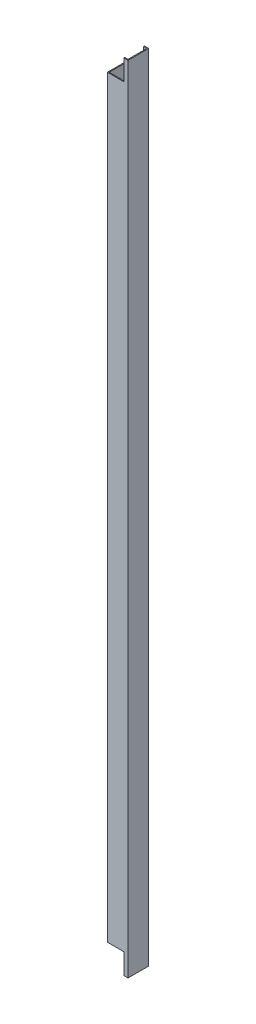
SolidWorks part; units mm, degrees
ref_plane "Front Plane" through (0, 0, 0) normal (0, 0, 1) x (1, 0, 0)
ref_plane "Top Plane" through (0, 0, 0) normal (0, 1, 0) x (1, 0, 0)
ref_plane "Right Plane" through (0, 0, 0) normal (1, 0, 0) x (0, 0, -1)
sketch "Sketch1" plane through (0, 0, 0) normal (0, 1, 0) x (1, 0, 0)
  line L0 (0, 0) -> (0, 50)
  line L1 (0, 50) -> (50, 50)
  line L2 (50, 50) -> (50, 0)
  line L3 (50, 0) -> (0, 0)
  line L4 (2.2, 47.8) -> (47.8, 47.8)
  line L5 (47.8, 47.8) -> (47.8, 2.2)
  line L6 (47.8, 2.2) -> (2.2, 2.2)
  line L7 (2.2, 2.2) -> (2.2, 47.8)
  dimension "D1" = 50
  dimension "D2" = 50
  dimension "D3" = 2.2
extrude "Boss-Extrude1" add sketch "Sketch1" along normal blind 1923
sketch "Sketch2" plane through (0, 0, 0) normal (0, 0, 1) x (1, 0, 0)
  line L0 (0, 0) -> (0, 50)
  line L1 (0, 1923) -> (0, 0) construction
  line L2 (0, 50) -> (40, 50)
  line L3 (40, 50) -> (40, 0)
  line L5 (40, 0) -> (0, 0)
  line L6 (0, 1923) -> (40, 1923)
  line L7 (0, 1923) -> (50, 1923) construction
  line L8 (40, 1923) -> (40, 1873)
  line L9 (40, 1873) -> (0, 1873)
  line L10 (0, 1873) -> (0, 1923)
  dimension "D1" = 50
  dimension "D2" = 40
  dimension "D3" = 50
  dimension "D4" = 40
extrude "Cut-Extrude2" cut sketch "Sketch2" against normal blind 50
equation "\"SquareTube_length\"=1923.0"
equation "\"D1@Boss-Extrude1\"=\"SquareTube_length\""
equation "\"SquareTube_inFront1_cutDepth50_R\"=0.5"
equation "\"D1@Sketch2\"= \"SquareTube_inFront11_cutDepth50_R\""
equation "\"SquareTube_inFront1_cutDepth50_L\"=0.5"
equation "\"D3@Sketch2\"= \"SquareTube_inFront11_cutDepth50_L\""
equation "\"CarBeamWidth\"=700.0"
equation "\"MetalSheet_3mm_length\"=5030.0"
equation "\"MetalSheet_3mm_width\"=1923.0"
equation "\"MetalSheet_3mm_FloorCut_L_length\"=1764.0"
equation "\"MetalSheet_3mm_FloorCut_L_disdance\"=1665.0"
equation "\"MetalSheet_3mm_FloorCut_R_length\"=1764.0"
equation "\"MetalSheet_3mm_FloorCut_R_disdance\"=1665.0"
equation "\"indoorHeight\"=1940.0"
equation "\"x\"=66.0"
equation "\"da\"=62.0"
equation "\"SquareTube_wheel_length\"= 750"
equation "\"channelSteel_length\"=5030.0"
equation "\"SquareTube_inFront2_cutDepth50_R\"=0.5"
equation "\"SquareTube_inFront2_cutDepth50_L\"=0.5"
equation "\"SquareTube_inFront3_cutDepth50_R\"=0.5"
equation "\"SquareTube_inFront3_cutDepth50_L\"=0.5"
equation "\"SquareTube_inFront4_cutDepth50_R\"=0.5"
equation "\"SquareTube_inFront4_cutDepth50_L\"=0.5"
equation "\"SquareTube_inFront5_cutDepth50_R\"=50"
equation "\"SquareTube_inFront5_cutDepth50_L\"=50"
equation "\"SquareTube_inFront6_cutDepth50_R\"=50"
equation "\"SquareTube_inFront6_cutDepth50_L\"=50"
equation "\"SquareTube_inFront7_cutDepth50_R\"=50"
equation "\"SquareTube_inFront7_cutDepth50_L\"=50"
equation "\"SquareTube_inFront8_cutDepth50_R\"=50"
equation "\"SquareTube_inFront8_cutDepth50_L\"=50"
equation "\"SquareTube_inFront9_cutDepth50_R\"=50"
equation "\"SquareTube_inFront9_cutDepth50_L\"=50"
equation "\"SquareTube_inFront10_cutDepth50_R\"=50"
equation "\"SquareTube_inFront10_cutDepth50_L\"=50"
equation "\"SquareTube_inBack1_cutDepth50_R\"=50"
equation "\"SquareTube_inBack1_cutDepth50_L\"=50"
equation "\"SquareTube_inBack2_cutDepth50_R\"=50"
equation "\"SquareTube_inBack2_cutDepth50_L\"=50"
equation "\"SquareTube_inBack3_cutDepth50_R\"=50"
equation "\"SquareTube_inBack3_cutDepth50_L\"=50"
equation "\"SquareTube_inBack4_cutDepth50_R\"=50"
equation "\"SquareTube_inBack4_cutDepth50_L\"=50"
equation "\"SquareTube_inBack5_cutDepth50_R\"=50"
equation "\"SquareTube_inBack5_cutDepth50_L\"=50"
equation "\"SquareTube_inBack6_cutDepth50_R\"=0.5"
equation "\"SquareTube_inBack6_cutDepth50_L\"=0.5"
equation "\"SquareTube_inFront11_cutDepth50_R\"=50"
equation "\"SquareTube_inFront11_cutDepth50_L\"=50"
equation "\"SquareTube_inFront12_cutDepth50_R\"=50"
equation "\"SquareTube_inFront12_cutDepth50_L\"=50"
equation "\"SquareTube_inFront13_cutDepth50_R\"=50"
equation "\"SquareTube_inFront13_cutDepth50_L\"=50"
equation "\"SquareTube_inFront14_cutDepth50_R\"=50"
equation "\"SquareTube_inFront14_cutDepth50_L\"=50"
equation "\"SquareTube_inBack7_cutDepth50_R\"=0.5"
equation "\"SquareTube_inBack7_cutDepth50_L\"=0.5"
equation "\"SquareTube_inBack8_cutDepth50_R\"=0.5"
equation "\"SquareTube_inBack8_cutDepth50_L\"=0.5"
